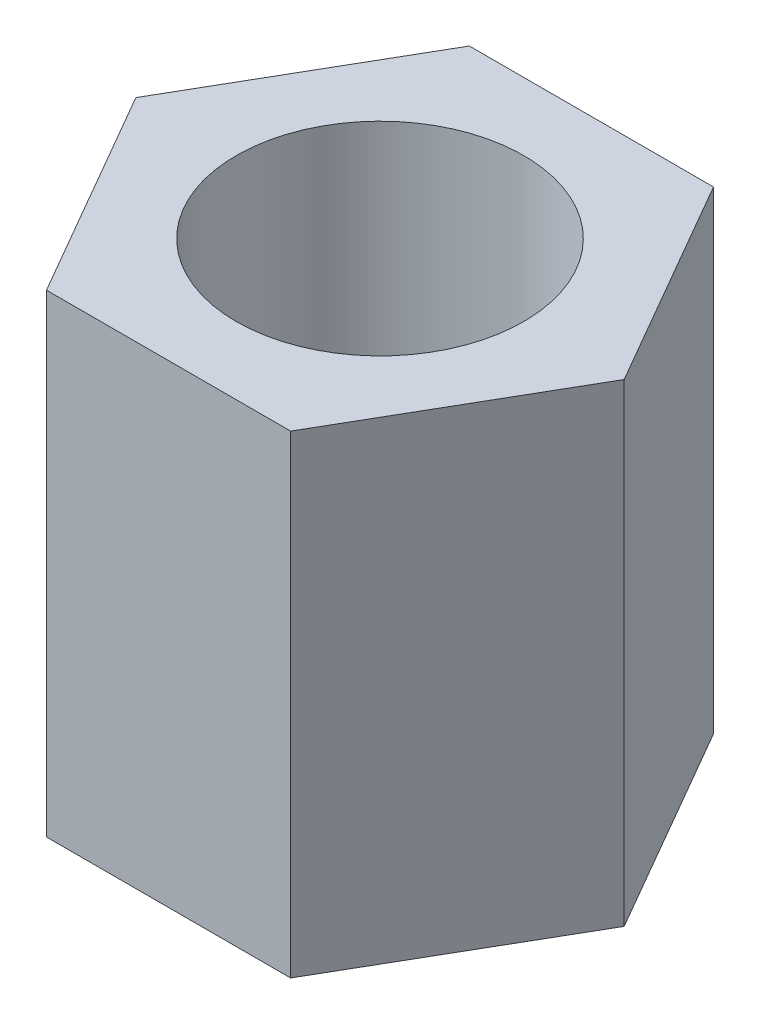
SolidWorks part; units mm, degrees
ref_plane "前视基准面" through (0, 0, 0) normal (0, 0, 1) x (1, 0, 0)
ref_plane "上视基准面" through (0, 0, 0) normal (0, 1, 0) x (1, 0, 0)
ref_plane "右视基准面" through (0, 0, 0) normal (1, 0, 0) x (0, 0, -1)
sketch "草图1" plane through (0, 0, 0) normal (0, 1, 0) x (1, 0, 0)
  line L1 (2.8868, 0) -> (1.4434, 2.5)
  line L2 (1.4434, 2.5) -> (-1.4434, 2.5)
  line L3 (-1.4434, 2.5) -> (-2.8868, 0)
  line L4 (-2.8868, 0) -> (-1.4434, -2.5)
  line L5 (-1.4434, -2.5) -> (1.4434, -2.5)
  line L6 (1.4434, -2.5) -> (2.8868, 0)
  circle A0 centre (0, 0) radius 1.7
  circle A1 centre (0, 0) radius 2.5 construction
  dimension "D1" = 3.4
  dimension "D2" = 5
extrude "凸台-拉伸1" add sketch "草图1" along normal blind 5.6
equation "\"h1\"= 5.6'铜柱的长度"
equation "\"D1@凸台-拉伸1\"=\"h1\""
equation "\"d\"= 3'螺丝直径(有补偿)"
equation "\"D1@草图1\"=\"d\"+0.4"
equation "\"h2\"= 15'铜柱的长度"
equation "\"h3\"= 30'铜柱的长度"
